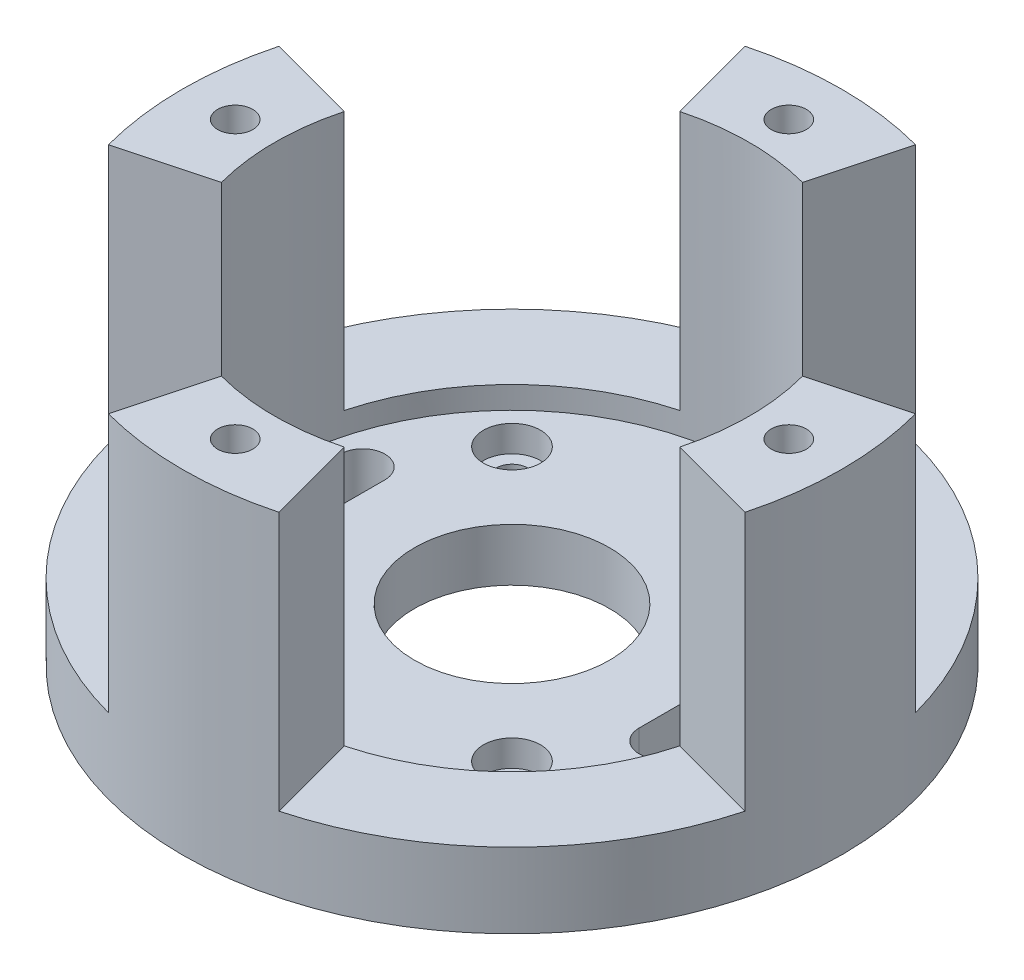
SolidWorks part; units mm, degrees
ref_plane "Front Plane" through (0, 0, 0) normal (0, 0, 1) x (1, 0, 0)
ref_plane "Top Plane" through (0, 0, 0) normal (0, 1, 0) x (1, 0, 0)
ref_plane "Right Plane" through (0, 0, 0) normal (1, 0, 0) x (0, 0, -1)
sketch "Sketch1" plane through (0, 0, 0) normal (0, 1, 0) x (1, 0, 0)
  line L1 (15.502, -15.5019) -> (-15.5019, -15.5019) construction
  line L2 (15.502, -15.5019) -> (15.502, 15.502) construction
  line L3 (15.502, 15.502) -> (-15.5019, 15.502) construction
  line L4 (-15.5019, -15.5019) -> (-15.5019, 15.502) construction
  line L5 (15.502, -15.5019) -> (-15.5019, 15.502) construction
  line L6 (15.502, 15.502) -> (-15.5019, -15.5019) construction
  circle A0 centre (0, 0) radius 37.5
  point P0 (0, 0)
  dimension "D2" = 75
  dimension "D1" = 31.0039
extrude "Boss-Extrude1" add sketch "Sketch1" along normal blind 6
hole_wizard "CBORE for M3 SHCS1" positions "Sketch2" profile "Sketch3" counterbore size "M3" standard "ANSI Metric"
sketch "Sketch2" plane through (0, 6, 0) normal (0, 1, 0) x (1, 0, 0)
  point P0 (-15.5019, 15.502)
  point P3 (15.502, 15.502)
  point P6 (15.502, -15.5019)
  point P9 (-15.5019, -15.5019)
sketch "Sketch3" plane through (-15.5019, 6, -15.502) normal (1, 0, 0) x (0, 0, 1)
  line L0 (0, 0) -> (0, 7.5817)
  line L1 (0, 7.5817) -> (1.8, 6.5001)
  line L2 (1.8, 6.5001) -> (1.8, 3)
  line L3 (1.8, 3) -> (3.25, 3)
  line L4 (3.25, 3) -> (3.25, 0)
  line L5 (3.25, 0) -> (0, 0)
  line L10 (0, 7.5817) -> (-1.8, 6.5001) construction
  line L11 (0, -6.35) -> (0, 107.95) construction
  dimension "Hole Dia." = 3.6
  dimension "Hole Depth" = 6.5001
  dimension "C'Bore Dia." = 6.5
  dimension "C'Bore Depth" = 3
  dimension "Drill Angle" = 118
sketch "Sketch7" plane through (0, 6, 0) normal (0, 1, 0) x (1, 0, 0)
  circle A0 centre (0, 0) radius 11.1016
  dimension "D1" = 22.2032
extrude "Cut-Extrude3" cut sketch "Sketch7" against normal through all
sketch "Sketch8" plane through (0, 6, 0) normal (0, 1, 0) x (1, 0, 0)
  circle A0 centre (0, 0) radius 27
  circle A2 centre (0, 0) radius 37.5
  circle A3 centre (0, 0) radius 37.5
  dimension "D1" = 54
  dimension "D2" = 0
extrude "Boss-Extrude2" add sketch "Sketch8" along normal offset from surface (32 mm away) 38 up to face at (0, 0, 11.1016)
sketch "Sketch5" plane through (0, 0, 0) normal (0, 1, 0) x (1, 0, 0)
  circle A0 centre (0, 0) radius 31.5 construction
  circle A1 centre (0, 31.5) radius 2.5273
  dimension "D1" = 63
  dimension "D2" = 5.0546
extrude "Cut-Extrude1" cut sketch "Sketch5" along normal blind 27.94
sketch "Sketch6" plane through (0, 27.94, 0) normal (0, -1, 0) x (-1, 0, 0)
  circle A0 centre (0, 31.5) radius 2
  dimension "D1" = 4
extrude "Cut-Extrude2" cut sketch "Sketch6" against normal through all contours A0
pattern_circular "CirPattern1" count 4 over 360 about axis through (0, 0, 0) along (0, 1, 0) of "Cut-Extrude2", "Cut-Extrude1"
sketch "Sketch9" plane through (0, 0, 0) normal (0, -1, 0) x (1, 0, 0)
  circle A0 centre (31.5, 0) radius 4
  circle A1 centre (0, -31.5) radius 4
  circle A2 centre (-31.5, 0) radius 4
  circle A3 centre (0, 31.5) radius 4
  dimension "D1" = 8
extrude "Cut-Extrude4" cut sketch "Sketch9" against normal offset from surface (24.14 mm away) 3.8 up to face at (0, 27.94, 33.5)
chamfer "Chamfer1" distance 0.762 angle 45 4 edges at (-31.5, 24.14, 2.5273) (0, 24.14, -28.9727) (31.5, 24.14, 2.5273) (0, 24.14, 34.0273)
sketch "Sketch10" plane through (0, 0, 0) normal (0, -1, 0) x (1, 0, 0)
  line L0 (-22, 5) -> (-22, -5) construction
  line L1 (-19.46, 5) -> (-19.46, -5)
  line L2 (-24.54, 5) -> (-24.54, -5)
  line L3 (-22, 0) -> (0, 0) construction
  arc A0 (-19.46, 5) -> (-24.54, 5) centre (-22, 5) ccw
  arc A1 (-24.54, -5) -> (-19.46, -5) centre (-22, -5) ccw
  point P2 (-22, 0)
  dimension "D1" = 5.08
  dimension "D2" = 10
  dimension "D3" = 22
extrude "Cut-Extrude5" cut sketch "Sketch10" against normal through all
mirror "Mirror1" about plane through (0, 0, 0) normal (1, 0, 0) of "Cut-Extrude5"
sketch "Sketch12" plane through (0, 38, 0) normal (0, 1, 0) x (1, 0, 0)
  line L0 (-37.5, 0) -> (0, 0) construction
  line L1 (0, 27) -> (0, 37.5) construction
  line L2 (-26.08, 6.9881) -> (-36.2222, 9.7057)
  line L3 (-6.9881, 26.08) -> (-9.7057, 36.2222)
  line L4 (-26.08, 6.9881) -> (0, 0) construction
  line L5 (0, 0) -> (-6.9881, 26.08) construction
  circle A0 centre (0, 0) radius 37.5 construction
  circle A1 centre (0, 0) radius 27 construction
  arc A2 (-6.9881, 26.08) -> (-26.08, 6.9881) centre (0, 0) ccw
  arc A3 (-9.7057, 36.2222) -> (-36.2222, 9.7057) centre (0, 0) ccw
  circle A4 centre (0, 0) radius 27 construction
  dimension "D1" = 15
  dimension "D2" = 15
extrude "Cut-Extrude6" cut sketch "Sketch12" against normal offset from surface (29.46 mm away) 2.54 up to face at (-22, 6, 0)
pattern_circular "CirPattern2" count 4 over 360 about axis through (0, 182.066, 0) along (0, -1, 0) of "Cut-Extrude6"
fillet "Fillet1" [suppressed] radius 12.7
fillet "Fillet2" [suppressed] radius 1.524
chamfer "Chamfer2" [suppressed] distance 0.762 angle 45
chamfer "Chamfer3" [suppressed] distance 0.254 angle 45
